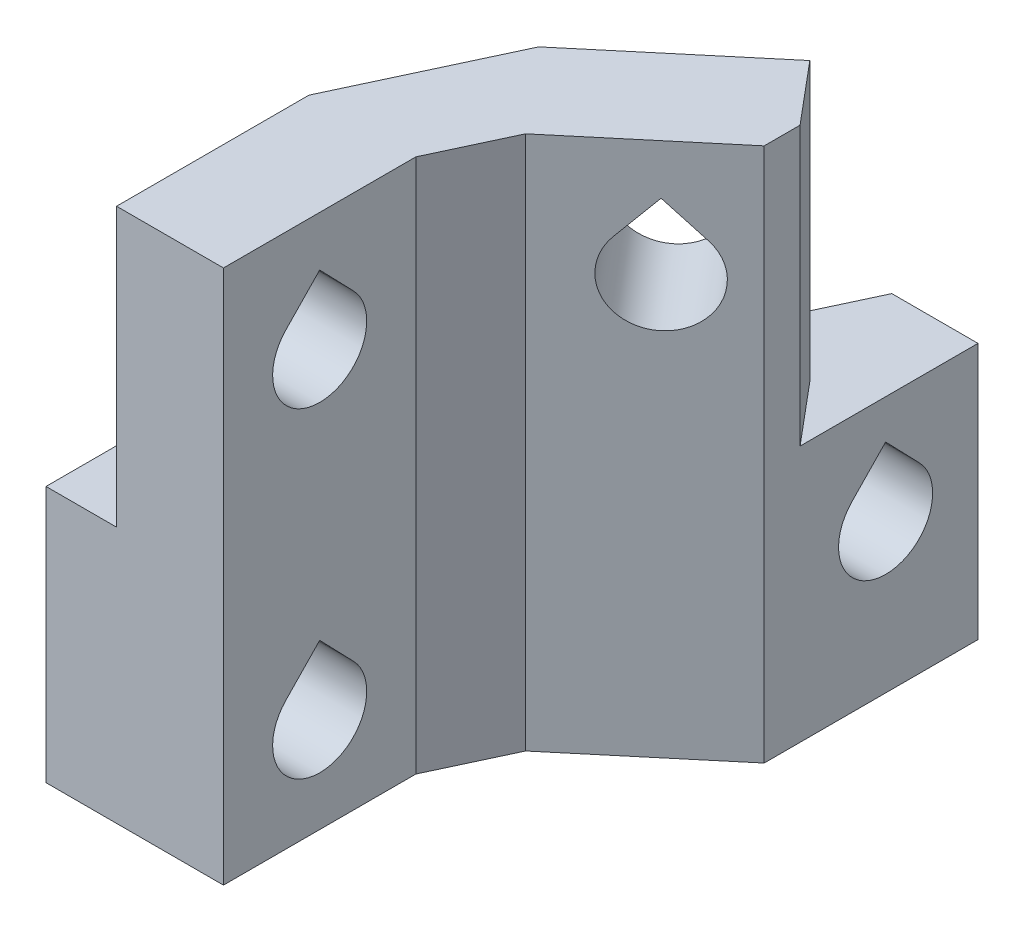
SolidWorks part; units mm, degrees
ref_plane "Front Plane" through (0, 0, 0) normal (0, 0, 1) x (1, 0, 0)
ref_plane "Top Plane" through (0, 0, 0) normal (0, 1, 0) x (1, 0, 0)
ref_plane "Right Plane" through (0, 0, 0) normal (1, 0, 0) x (0, 0, -1)
ref_plane "Plane1" through (0, -17, 0) normal (0, -1, 0) x (1, 0, 0)
sketch "Sketch1" plane through (0, -17, 0) normal (0, -1, 0) x (1, 0, 0)
  line L0 (16, 15) -> (3.3, 15)
  line L1 (3.3, 15) -> (3.3, 6)
  line L2 (3.3, 6) -> (11.969, -12.5907)
  line L3 (11.969, -12.5907) -> (16, -12.5907)
  line L4 (16, -12.5907) -> (16, 15)
extrude "Boss-Extrude1" add sketch "Sketch1" against normal blind 12
sketch "Sketch2" plane through (0, -5, 0) normal (0, 1, 0) x (-1, 0, 0)
  line L0 (-16, 15) -> (-3.3, 15)
  line L1 (-3.3, 15) -> (-3.3, 6)
  line L2 (-3.3, 6) -> (-6.7175, -1.3288)
  line L3 (-6.7175, -1.3288) -> (-13.6119, -7.1139)
  line L4 (-13.6119, -7.1139) -> (-16, -4.2678)
  line L5 (-16, -4.2678) -> (-16, 15)
extrude "Boss-Extrude2" add sketch "Sketch2" along normal blind 13
sketch "Sketch3" plane through (3.3, 0, 0) normal (-1, 0, 0) x (0, 0, 1)
  line L0 (6, -17) -> (6, -5)
  line L1 (6, -5) -> (15, -5)
  line L2 (15, -5) -> (15, -17)
  line L3 (15, -17) -> (6, -17)
extrude "Boss-Extrude3" add sketch "Sketch3" along normal blind 3.3
sketch "Sketch4" plane through (0, -17, 0) normal (0, -1, 0) x (1, 0, 0)
  line L0 (16, 15) -> (8.3, 15)
  line L1 (8.3, 15) -> (8.3, 3.8704)
  line L2 (8.3, 3.8704) -> (16, -2.5907)
  line L3 (16, -2.5907) -> (16, 15)
extrude "Cut-Extrude1" cut sketch "Sketch4" against normal through all
sketch "Sketch5" plane through (8.3, 0, 0) normal (1, 0, 0) x (0, 0, -1)
  line L0 (-8.9175, -10.9718) -> (-10.5, -9.333)
  line L1 (-10.5, -9.333) -> (-12.0825, -10.9718)
  arc A0 (-12.0825, -10.9718) -> (-8.9175, -10.9718) centre (-10.5, -12.5) ccw
extrude "Cut-Extrude2" cut sketch "Sketch5" against normal through all
sketch "Sketch6" plane through (8.3, 0, 0) normal (1, 0, 0) x (0, 0, -1)
  line L0 (-8.9175, 4.0282) -> (-10.5, 5.667)
  line L1 (-10.5, 5.667) -> (-12.0825, 4.0282)
  arc A0 (-12.0825, 4.0282) -> (-8.9175, 4.0282) centre (-10.5, 2.5) ccw
extrude "Cut-Extrude3" cut sketch "Sketch6" against normal through all
sketch "Sketch7" plane through (5.3351, 0, 6.3582) normal (0.6428, 0, 0.766) x (0.766, 0, -0.6428)
  line L0 (12.0826, 4.0282) -> (10.5, 5.667)
  line L1 (10.5, 5.667) -> (8.9175, 4.0282)
  arc A0 (8.9175, 4.0282) -> (12.0826, 4.0282) centre (10.5, 2.5) ccw
extrude "Cut-Extrude4" cut sketch "Sketch7" against normal through all
sketch "Sketch8" plane through (16, 0, 0) normal (1, 0, 0) x (0, 0, -1)
  line L0 (9.8523, -8.4718) -> (8.2698, -6.833)
  line L1 (8.2698, -6.833) -> (6.6872, -8.4718)
  arc A0 (6.6872, -8.4718) -> (9.8523, -8.4718) centre (8.2698, -10) ccw
extrude "Cut-Extrude5" cut sketch "Sketch8" against normal through all
chamfer "Chamfer1" distance 2.1296 angle 25 1 edges at (8.3, -4.5, 3.8704)
